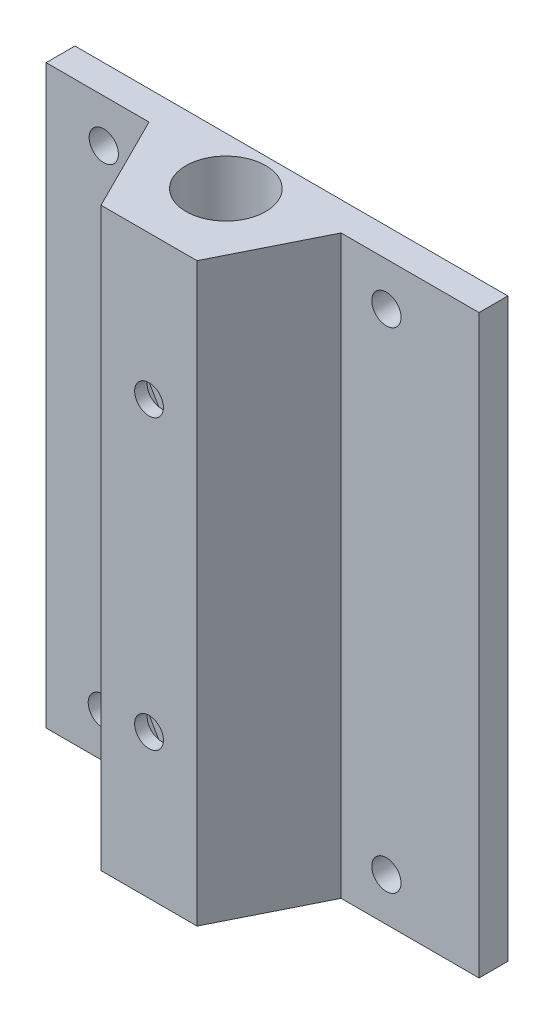
SolidWorks part; units mm, degrees
ref_plane "前视基准面" through (0, 0, 0) normal (0, 0, 1) x (1, 0, 0)
ref_plane "上视基准面" through (0, 0, 0) normal (0, 1, 0) x (1, 0, 0)
ref_plane "右视基准面" through (0, 0, 0) normal (1, 0, 0) x (0, 0, -1)
other "Configuration Table"
sketch "草图1" plane through (0, 0, 0) normal (0, 0, 1) x (1, 0, 0)
  line L0 (14.927, 60) -> (14.927, 0)
  line L1 (60, 60) -> (6.75, 60)
  line L2 (60, 60) -> (60, 0)
  line L3 (60, 0) -> (6.75, 0)
  line L4 (6.75, 60) -> (6.75, 0)
  circle A0 centre (50.3515, 55.5) radius 1.525
  circle A2 centre (20.927, 55.5) radius 1.525
  circle A3 centre (20.8311, 4.5) radius 1.525
  circle A4 centre (50.3515, 4.5) radius 1.525
  dimension "D1" = 6
  dimension "D2" = 9.6485
extrude "凸台-拉伸1" add sketch "草图1" along normal blind 3 contours L3 L2 L1 L0 A4 A3 A2 A0
sketch "草图2" plane through (0, 0, 3) normal (0, 0, 1) x (1, 0, 0)
  line L1 (50.3515, 55.5) -> (20.927, 55.5) construction
  line L2 (35.6392, 60) -> (35.6392, 0) construction
  line L3 (60, 60) -> (14.927, 60) construction
  line L4 (60, 0) -> (14.927, 0) construction
  line L6 (30.6392, 60) -> (40.6392, 60)
  line L7 (30.6392, 60) -> (30.6392, 0)
  line L8 (30.6392, 0) -> (40.6392, 0)
  line L9 (40.6392, 60) -> (40.6392, 0)
  line L10 (30.6392, 60) -> (40.6392, 0) construction
  line L11 (30.6392, 0) -> (40.6392, 60) construction
  point P10 (35.6392, 30)
  dimension "D1" = 10
extrude "凸台-拉伸2" add sketch "草图2" along normal blind 10
hole_wizard "孔1" positions "草图3" profile "草图4" legacy end condition up to next
sketch "草图3" plane through (0, 0, 0) normal (0, -1, 0) x (-1, 0, 0)
  line L0 (-35.6392, -13) -> (-35.6392, 0) construction
  line L1 (-30.6392, -13) -> (-40.6392, -13) construction
  line L2 (-60, 0) -> (-14.927, 0) construction
  point P0 (-35.6392, -5)
  dimension "D1" = 5
sketch "草图4" plane through (35.6392, 0, 5) normal (1, 0, 0) x (0, 0, -1)
  line L0 (0, 0) -> (0, 60)
  line L1 (0, 60) -> (4.15, 60)
  line L2 (4.15, 60) -> (4.15, 0)
  line L3 (4.15, 0) -> (0, 0)
  line L4 (0, 110) -> (0, -10) construction
  dimension "直径" = 8.3
  dimension "深度" = 60
sketch "草图5" plane through (0, 0, 0) normal (0, -1, 0) x (1, 0, 0)
  line L0 (30.6392, 13) -> (25.6392, 3)
  line L1 (30.6392, 3) -> (14.927, 3) construction
  line L2 (40.6392, 13) -> (45.6392, 3)
  line L5 (60, 3) -> (40.6392, 3) construction
  line L6 (45.6392, 3) -> (40.6392, 3)
  line L7 (40.6392, 3) -> (40.6392, 13)
  line L8 (25.6392, 3) -> (30.6392, 3)
  line L9 (30.6392, 3) -> (30.6392, 13)
  dimension "D1" = 5
  dimension "D2" = 5
extrude "凸台-拉伸3" add sketch "草图5" against normal blind 60
ref_plane "基准面1" through (0, 0, 11) normal (0, 0, 1) x (1, 0, 0)
sketch "草图7" plane through (0, 0, 11) normal (0, 0, 1) x (1, 0, 0)
  line L0 (35.6392, 60) -> (35.6392, 0) construction
  line L1 (40.6392, 60) -> (30.6392, 60) construction
  line L2 (30.6392, 0) -> (40.6392, 0) construction
  line L3 (37.3135, 12.1) -> (38.9879, 15)
  line L4 (38.9879, 45) -> (37.3135, 47.9)
  line L5 (37.3135, 47.9) -> (33.9649, 47.9)
  line L6 (33.9649, 47.9) -> (32.2906, 45)
  line L7 (32.2906, 45) -> (33.9649, 42.1)
  line L8 (33.9649, 42.1) -> (37.3135, 42.1)
  line L9 (37.3135, 42.1) -> (38.9879, 45)
  line L10 (33.9649, 12.1) -> (37.3135, 12.1)
  line L11 (32.2906, 15) -> (33.9649, 12.1)
  line L12 (33.9649, 17.9) -> (32.2906, 15)
  line L13 (37.3135, 17.9) -> (33.9649, 17.9)
  line L14 (38.9879, 15) -> (37.3135, 17.9)
  circle A0 centre (35.6392, 45) radius 2.9 construction
  dimension "D1" = 15
  dimension "D2" = 2
extrude "切除-拉伸1" cut sketch "草图7" against normal mid plane 1.4
hole_wizard "孔2" positions "草图8" profile "草图9" legacy
sketch "草图8" plane through (0, 0, 13) normal (0, 0, 1) x (1, 0, 0)
  line L0 (35.6392, 60) -> (35.6392, 0) construction
  line L1 (40.6392, 60) -> (30.6392, 60) construction
  line L2 (30.6392, 0) -> (40.6392, 0) construction
  point P0 (35.6392, 45)
  point P2 (35.6392, 15)
  point P12 (35.6392, 50.2564)
  point P13 (35.6392, 11.039)
  dimension "D1" = 15
  dimension "D2" = 15
sketch "草图9" plane through (35.6392, 45, 13) normal (1, 0, 0) x (0, -1, 0)
  line L0 (0, 0) -> (0, 5)
  line L1 (0, 5) -> (1.5, 5)
  line L2 (1.5, 5) -> (1.5, 0)
  line L3 (1.5, 0) -> (0, 0)
  line L4 (0, 110) -> (0, -10) construction
  dimension "直径" = 3
  dimension "深度" = 5
